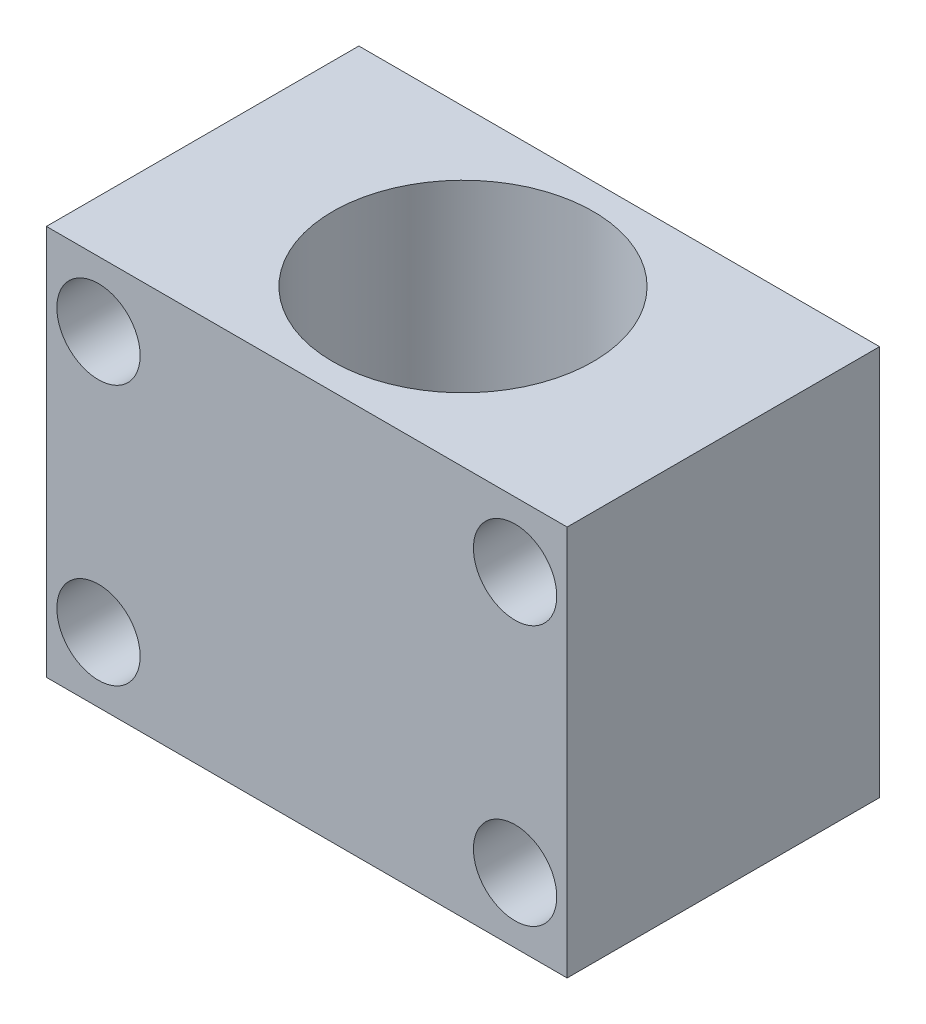
SolidWorks part; units mm, degrees
ref_plane "Płaszczyzna przednia" through (0, 0, 0) normal (0, 0, 1) x (1, 0, 0)
ref_plane "Płaszczyzna górna" through (0, 0, 0) normal (0, 1, 0) x (1, 0, 0)
ref_plane "Płaszczyzna prawa" through (0, 0, 0) normal (1, 0, 0) x (0, 0, -1)
sketch "Szkic1" plane through (0, 0, 0) normal (0, 1, 0) x (1, 0, 0)
  line L1 (-10, -6) -> (10, -6)
  line L2 (-10, -6) -> (-10, 6)
  line L3 (-10, 6) -> (10, 6)
  line L4 (10, -6) -> (10, 6)
  line L5 (0, 6) -> (0, -6) construction
  line L6 (-10, 0) -> (10, 0) construction
  circle A0 centre (0, 0) radius 5
  point P0 (0, 0)
  dimension "D1" = 10
  dimension "D2" = 20
  dimension "D3" = 12
extrude "Dodanie-wyciągnięcie1" add sketch "Szkic1" along normal blind 15
sketch "Szkic2" plane through (0, 0, 6) normal (0, 0, 1) x (1, 0, 0)
  line L0 (-8, 15) -> (-8, 0) construction
  line L1 (-10, 15) -> (10, 15) construction
  line L2 (-10, 0) -> (10, 0) construction
  line L3 (-10, 15) -> (-10, 0) construction
  line L4 (-10, 7.5) -> (10, 7.5) construction
  line L5 (10, 15) -> (10, 0) construction
  line L6 (0, 15) -> (0, 0) construction
  point P8 (-8, 12.5)
  point P9 (-8, 2.5)
  point P16 (0, 0)
  point P17 (8, 2.5)
  point P18 (8, 12.5)
  dimension "D1" = 2
  dimension "D2" = 10
hole_wizard "Otwór Ø3.2 (3.2)1" positions "Szkic2" profile "Szkic3" hole size "Ø3.2" standard "DIN" end condition up to next
sketch "Szkic3" plane through (8, 12.5, 6) normal (1, 0, 0) x (0, -1, 0)
  line L0 (0, 0) -> (0, 12)
  line L1 (0, 12) -> (1.6, 12)
  line L2 (1.6, 12) -> (1.6, 0)
  line L5 (1.6, 0) -> (0, 0)
  line L11 (0, -6.35) -> (0, 107.95) construction
  dimension "Średnica otworu na wylot" = 3.2
  dimension "Głębokość otworu na wylot" = 12
